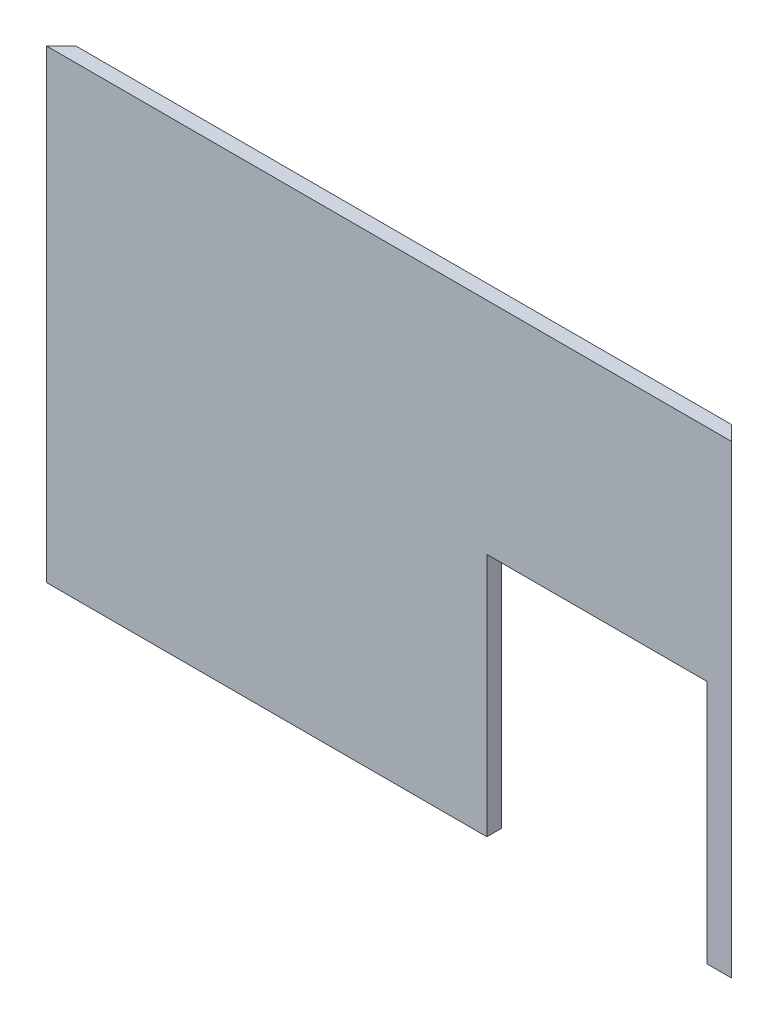
SolidWorks part; units mm, degrees
ref_plane "Front Plane" through (0, 0, 0) normal (0, 0, 1) x (1, 0, 0)
ref_plane "Top Plane" through (0, 0, 0) normal (0, 1, 0) x (1, 0, 0)
ref_plane "Right Plane" through (0, 0, 0) normal (1, 0, 0) x (0, 0, -1)
sketch "Sketch1" plane through (0, 0, 0) normal (0, 1, 0) x (1, 0, 0)
  line L1 (70, -1.5) -> (-70, -1.5)
  line L2 (70, -1.5) -> (70, 1.5)
  line L3 (70, 1.5) -> (-70, 1.5)
  line L4 (-70, -1.5) -> (-70, 1.5)
  line L5 (70, -1.5) -> (-70, 1.5) construction
  line L6 (70, 1.5) -> (-70, -1.5) construction
  point P0 (0, 0)
  dimension "D1" = 140
  dimension "D2" = 3
extrude "Boss-Extrude1" add sketch "Sketch1" along normal blind 95
sketch "º" plane through (0, 95, 0) normal (0, 1, 0) x (1, 0, 0)
  line L0 (70, -1.5) -> (70, 1.5)
  line L1 (70, 1.5) -> (67, 1.5)
  line L2 (70, 1.5) -> (-70, 1.5) construction
  line L3 (67, 1.5) -> (70, -1.5)
  line L4 (-70, -1.5) -> (-70, 1.5)
  line L5 (-70, 1.5) -> (-67, 1.5)
  line L6 (-67, 1.5) -> (-70, -1.5)
  dimension "D1" = 45
  dimension "D2" = 45
extrude "Cut-Extrude1" cut sketch "º" against normal blind 95
sketch "Sketch4" plane through (0, 0, 1.5) normal (0, 0, 1) x (1, 0, 0)
  line L0 (70, 95) -> (70, 0) construction
  line L1 (20, 50) -> (65, 50)
  line L2 (20, 50) -> (20, 0)
  line L3 (20, 0) -> (65, 0)
  line L4 (65, 50) -> (65, 0)
  dimension "D1" = 50
  dimension "D2" = 45
  dimension "D3" = 5
extrude "Cut-Extrude3" cut sketch "Sketch4" against normal blind 10
